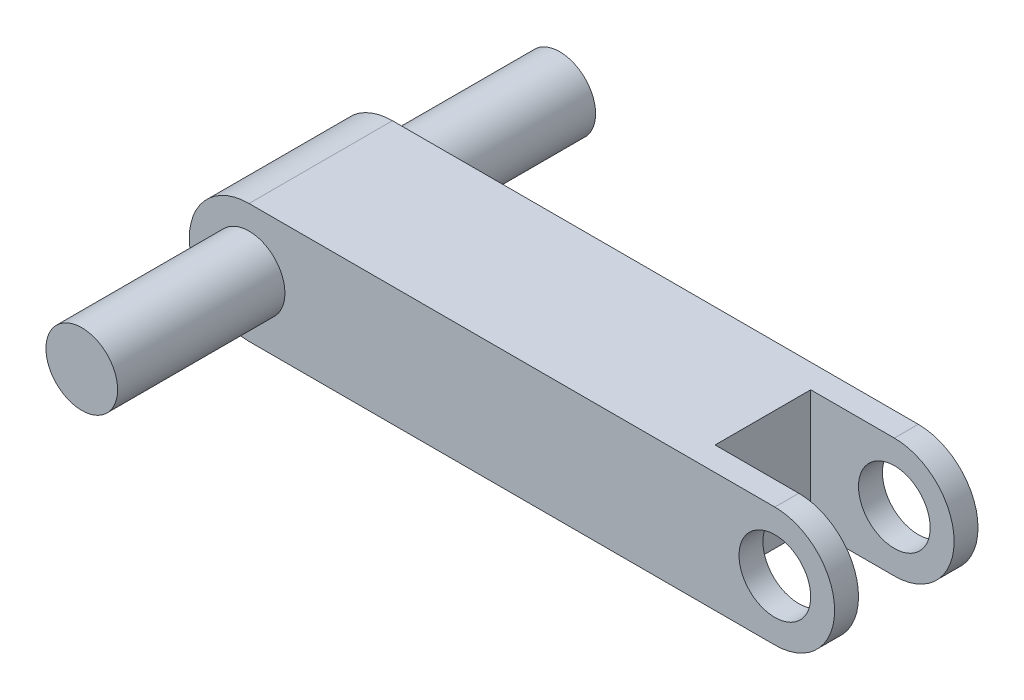
SolidWorks part; units mm, degrees
material "1023 Carbon Steel Sheet (SS)"
ref_plane "Front Plane" through (0, 0, 0) normal (0, 0, 1) x (1, 0, 0)
ref_plane "Top Plane" through (0, 0, 0) normal (0, 1, 0) x (1, 0, 0)
ref_plane "Right Plane" through (0, 0, 0) normal (1, 0, 0) x (0, 0, -1)
sketch "Sketch1" plane through (0, 0, 0) normal (0, 0, 1) x (1, 0, 0)
  line L0 (-91.3432, -0.3731) -> (128.6568, -0.3731) construction
  line L1 (-91.3432, 24.6269) -> (128.6568, 24.6269)
  line L2 (-91.3432, -25.3731) -> (128.6568, -25.3731)
  arc A0 (-91.3432, 24.6269) -> (-91.3432, -25.3731) centre (-91.3432, -0.3731) ccw
  arc A1 (128.6568, -25.3731) -> (128.6568, 24.6269) centre (128.6568, -0.3731) ccw
  point P3 (18.6568, -0.3731)
  dimension "D1" = 50
  dimension "D2" = 220
extrude "Boss-Extrude1" add sketch "Sketch1" along normal blind 60
sketch "Sketch2" plane through (0, 0, 60) normal (0, 0, 1) x (1, 0, 0)
  circle A2 centre (-91.3432, -0.3731) radius 15
extrude "Boss-Extrude2" add sketch "Sketch2" along normal blind 70
sketch "Sketch3" plane through (0, 0, 0) normal (0, 0, -1) x (-1, 0, 0)
  circle A2 centre (91.3432, -0.3731) radius 15
extrude "Boss-Extrude3" add sketch "Sketch3" along normal blind 70
sketch "Sketch4" plane through (0, 24.6269, 0) normal (0, 1, 0) x (1, 0, 0)
  line L4 (153.6568, -60) -> (153.6568, 0) construction
  line L5 (93.6568, -10) -> (153.6568, -10)
  line L6 (93.6568, -10) -> (93.6568, -50)
  line L7 (93.6568, -50) -> (153.6568, -50)
  line L8 (153.6568, -10) -> (153.6568, -50)
extrude "Cut-Extrude1" cut sketch "Sketch4" against normal blind 75
sketch "Sketch5" plane through (0, 0, 60) normal (0, 0, 1) x (1, 0, 0)
  circle A2 centre (128.6568, -0.3731) radius 15
extrude "Cut-Extrude2" cut sketch "Sketch5" against normal blind 75
sketch "Sketch6" plane through (0, 24.6269, 0) normal (0, 1, 0) x (1, 0, 0)
  line L0 (-76.3432, 70) -> (-106.3432, 70) construction
  line L1 (-106.3432, -130) -> (-76.3432, -130) construction
  line L2 (-76.3432, 70) -> (-106.3432, 70)
  line L3 (-106.3432, -130) -> (-76.3432, -130)
  line L8 (93.6568, -50) -> (93.6568, -10)
  line L9 (93.6568, -10) -> (128.6568, -10)
  line L10 (128.6568, -10) -> (128.6568, 0)
  line L11 (128.6568, 0) -> (-91.3432, 0)
  line L12 (-91.3432, 0) -> (-91.3432, -60)
  line L13 (-91.3432, -60) -> (128.6568, -60)
  line L14 (128.6568, -60) -> (128.6568, -50)
  line L15 (128.6568, -50) -> (93.6568, -50)
  line L16 (93.6568, -50) -> (93.6568, -10)
  line L17 (93.6568, -10) -> (128.6568, -10)
  line L18 (128.6568, -10) -> (128.6568, 0)
  line L19 (128.6568, 0) -> (-91.3432, 0)
  line L20 (-91.3432, 0) -> (-91.3432, -60)
  line L21 (-91.3432, -60) -> (128.6568, -60)
  line L22 (128.6568, -60) -> (128.6568, -50)
  line L23 (128.6568, -50) -> (93.6568, -50)
  dimension "D1" = 0
